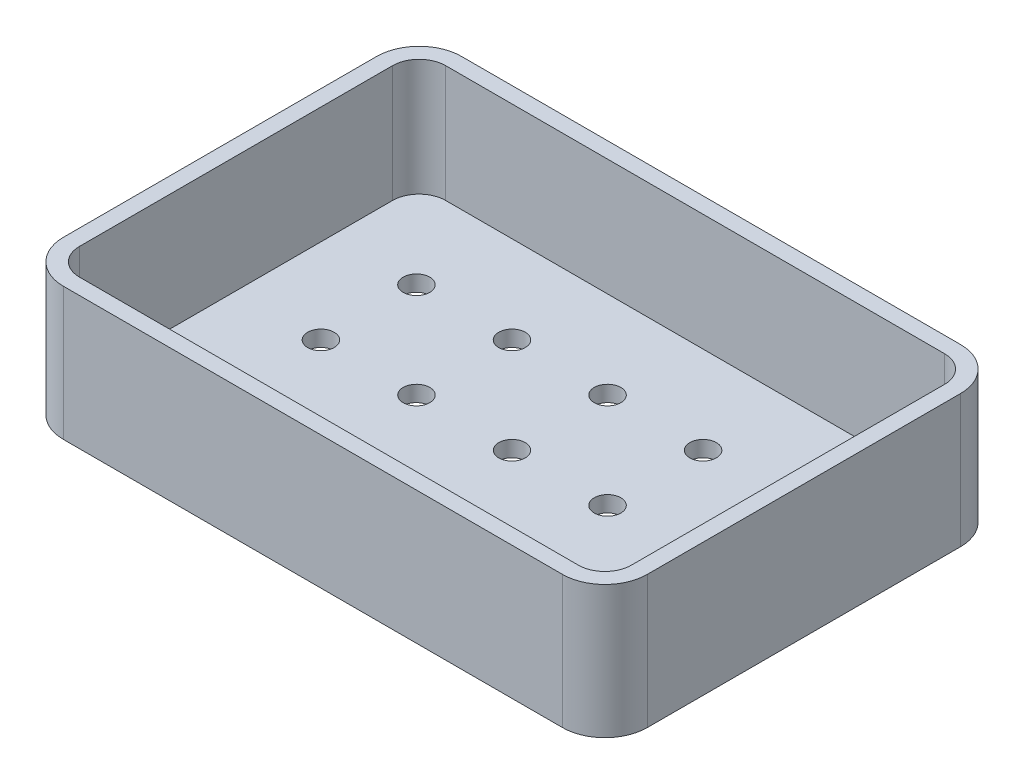
SolidWorks part; units mm, degrees
ref_plane "前视基准面" through (0, 0, 0) normal (0, 0, 1) x (1, 0, 0)
ref_plane "上视基准面" through (0, 0, 0) normal (0, 1, 0) x (1, 0, 0)
ref_plane "右视基准面" through (0, 0, 0) normal (1, 0, 0) x (0, 0, -1)
sketch "草图1" plane through (0, 0, 0) normal (0, 1, 0) x (1, 0, 0)
  line L0 (-47, 37.5) -> (47, 37.5)
  line L1 (55, 29.5) -> (55, -29.5)
  line L2 (47, -37.5) -> (-47, -37.5)
  line L3 (-55, -29.5) -> (-55, 29.5)
  arc A0 (-55, 29.5) -> (-47, 37.5) centre (-47, 29.5) cw
  arc A1 (47, 37.5) -> (55, 29.5) centre (47, 29.5) cw
  arc A2 (55, -29.5) -> (47, -37.5) centre (47, -29.5) cw
  arc A3 (-47, -37.5) -> (-55, -29.5) centre (-47, -29.5) cw
extrude "凸台-拉伸1" add sketch "草图1" against normal blind 25
ref_plane "基准面1" through (0, -22, 0) normal (0, 1, 0) x (1, 0, 0)
sketch "草图2" plane through (0, -22, 0) normal (0, 1, 0) x (1, 0, 0)
  line L0 (-47, 34.5) -> (47, 34.5)
  line L1 (52, 29.5) -> (52, -29.5)
  line L2 (47, -34.5) -> (-47, -34.5)
  line L3 (-52, -29.5) -> (-52, 29.5)
  arc A0 (-52, 29.5) -> (-47, 34.5) centre (-47, 29.5) cw
  arc A1 (47, 34.5) -> (52, 29.5) centre (47, 29.5) cw
  arc A2 (52, -29.5) -> (47, -34.5) centre (47, -29.5) cw
  arc A3 (-47, -34.5) -> (-52, -29.5) centre (-47, -29.5) cw
extrude "切除-拉伸1" cut sketch "草图2" along normal blind 22
ref_plane "基准面2" through (0, -25, 0) normal (0, 1, 0) x (1, 0, 0)
sketch "草图3" plane through (0, -25, 0) normal (0, 1, 0) x (1, 0, 0)
  circle A0 centre (-36, 18) radius 2.5
  circle A1 centre (-18, 18) radius 2.5
  circle A2 centre (0, 18) radius 2.5
  circle A3 centre (18, 18) radius 2.5
  circle A4 centre (36, 18) radius 2.5
  circle A5 centre (-36, 0) radius 2.5
  circle A6 centre (-18, 0) radius 2.5
  circle A7 centre (0, 0) radius 2.5
  circle A8 centre (18, 0) radius 2.5
  circle A9 centre (36, 0) radius 2.5
  circle A10 centre (-36, -18) radius 2.5
  circle A11 centre (-18, -18) radius 2.5
  circle A12 centre (0, -18) radius 2.5
  circle A13 centre (18, -18) radius 2.5
  circle A14 centre (36, -18) radius 2.5
extrude "切除-拉伸2" cut sketch "草图3" along normal through all
